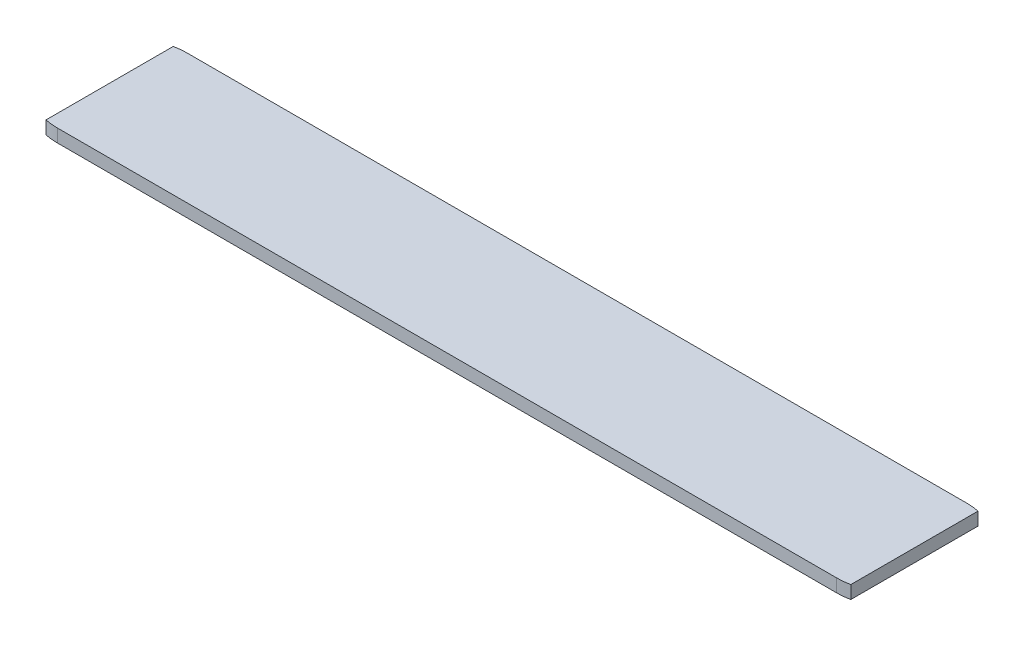
SolidWorks part; units mm, degrees
ref_plane "Front Plane" through (0, 0, 0) normal (0, 0, 1) x (1, 0, 0)
ref_plane "Top Plane" through (0, 0, 0) normal (0, 1, 0) x (1, 0, 0)
ref_plane "Right Plane" through (0, 0, 0) normal (1, 0, 0) x (0, 0, -1)
sketch "Sketch1" plane through (0, 0, 0) normal (0, 1, 0) x (1, 0, 0)
  line L0 (-47.625, 0) -> (47.625, 0) construction
  line L1 (-47.625, 7.9375) -> (47.625, 7.9375)
  line L2 (-47.625, -7.9375) -> (47.625, -7.9375)
  arc A0 (-47.625, 7.9375) -> (-47.625, -7.9375) centre (-47.625, 0) ccw
  arc A1 (47.625, -7.9375) -> (47.625, 7.9375) centre (47.625, 0) ccw
  point P3 (0, 0)
  point P8 (0, 0)
  dimension "D1" = 7.9375
  dimension "D2" = 95.25
extrude "Boss-Extrude1" add sketch "Sketch1" along normal blind 1.5875
sketch "Sketch2" plane through (0, 1.5875, 0) normal (0, 1, 0) x (1, 0, 0)
  line L1 (-49.2125, 7.9375) -> (49.2125, 7.9375)
  line L2 (-49.2125, 7.9375) -> (-49.2125, -7.9375)
  line L3 (-49.2125, -7.9375) -> (49.2125, -7.9375)
  line L4 (49.2125, 7.9375) -> (49.2125, -7.9375)
  line L5 (-64.4367, 17.9327) -> (67.3799, 17.9327)
  line L6 (-64.4367, 17.9327) -> (-64.4367, -18.648)
  line L7 (-64.4367, -18.648) -> (67.3799, -18.648)
  line L8 (67.3799, 17.9327) -> (67.3799, -18.648)
  dimension "D1" = 98.425
  dimension "D2" = 49.2125
  dimension "D3" = 15.875
  dimension "D4" = 7.9375
extrude "Cut-Extrude1" cut sketch "Sketch2" against normal blind 2.54
